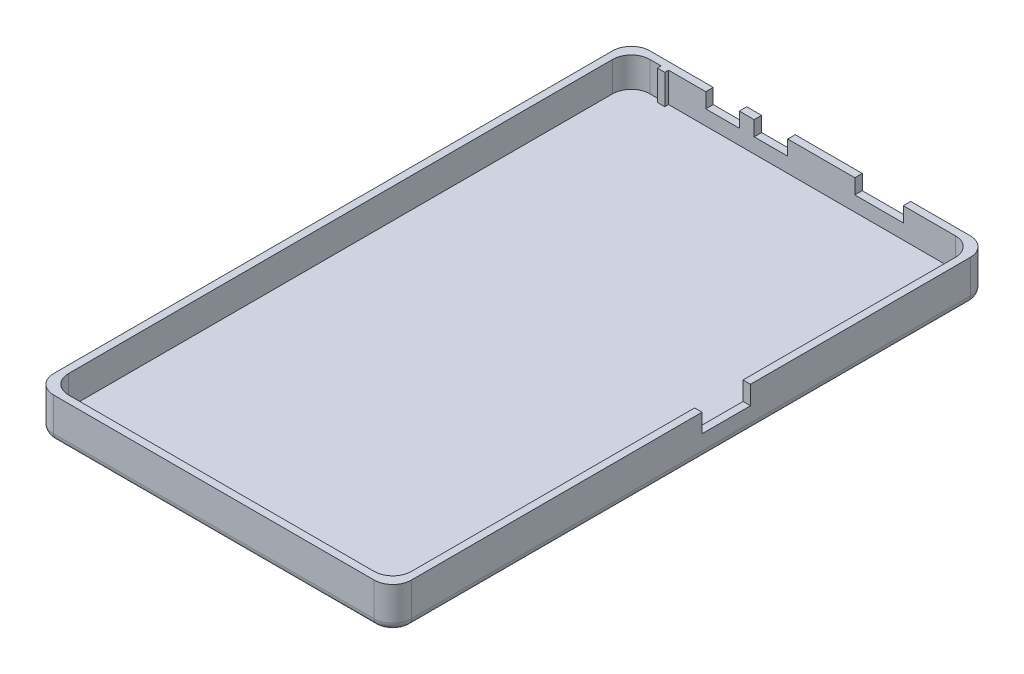
SolidWorks part; units mm, degrees
ref_plane "Front" through (0, 0, 0) normal (0, 0, 1) x (1, 0, 0)
ref_plane "Top" through (0, 0, 0) normal (0, 1, 0) x (1, 0, 0)
ref_plane "Right" through (0, 0, 0) normal (1, 0, 0) x (0, 0, -1)
sketch "草图1" plane through (0, 0, 0) normal (0, 1, 0) x (1, 0, 0)
  line L1 (-48, 80) -> (48, 80)
  line L2 (-48, 80) -> (-48, -80)
  line L3 (-48, -80) -> (48, -80)
  line L4 (48, 80) -> (48, -80)
  line L5 (-48, 80) -> (48, -80) construction
  line L6 (-48, -80) -> (48, 80) construction
  point P0 (0, 0)
  dimension "D1" = 96
  dimension "D2" = 160
extrude "凸台-拉伸1" add sketch "草图1" along normal blind 11
fillet "圆角1" radius 5 1 edges at (-48, 5.5, -80)
fillet "圆角2" radius 5 1 edges at (48, 5.5, -80)
fillet "圆角3" radius 5 1 edges at (48, 5.5, 80)
fillet "圆角4" radius 5 1 edges at (-48, 5.5, 80)
fillet "圆角5" radius 2 8 edges at (-46.5355, 0, 78.5355) (-48, 0, 0) (-46.5355, 0, -78.5355) (0, 0, -80) (46.5355, 0, -78.5355) (48, 0, 0) (46.5355, 0, 78.5355) (0, 0, 80)
sketch "草图2" plane through (0, 11, 0) normal (0, 1, 0) x (1, 0, 0)
  line L0 (-36, 78) -> (41, 78)
  line L1 (-41, 78) -> (-38, 78)
  line L2 (-46, 73) -> (-46, -73)
  line L3 (-41, -78) -> (41, -78)
  line L4 (46, 73) -> (46, -73)
  line L5 (-46, 78) -> (46, -78) construction
  line L6 (-46, -78) -> (46, 78) construction
  line L8 (-38, 78) -> (-38, 77)
  line L9 (-38, 77) -> (-36, 77)
  line L10 (-36, 78) -> (-36, 77)
  arc A0 (-46, 73) -> (-41, 78) centre (-41, 73) cw
  arc A1 (41, 78) -> (46, 73) centre (41, 73) cw
  arc A2 (-41, -78) -> (-46, -73) centre (-41, -73) cw
  arc A3 (41, -78) -> (46, -73) centre (41, -73) ccw
  point P0 (0, 0)
  dimension "D3" = 5
  dimension "D4" = 5
  dimension "D5" = 5
  dimension "D6" = 5
  dimension "D1" = 92
  dimension "D2" = 156
  dimension "D7" = 8
  dimension "D8" = 2
  dimension "D9" = 1
extrude "切除-拉伸1" cut sketch "草图2" against normal blind 8
sketch "草图3" plane through (0, 0, -78) normal (0, 0, 1) x (1, 0, 0)
  line L0 (-36, 3) -> (-36, 11) construction
  line L1 (-26, 11) -> (-17, 11)
  line L2 (-26, 11) -> (-26, 7)
  line L3 (-26, 7) -> (-17, 7)
  line L4 (-17, 11) -> (-17, 7)
  line L6 (-13, 11) -> (-4, 11)
  line L7 (-13, 11) -> (-13, 7)
  line L8 (-13, 7) -> (-4, 7)
  line L9 (-4, 11) -> (-4, 7)
  line L10 (11.7779, 58.6535) -> (20.7779, 58.6535)
  line L11 (11.7779, 58.6535) -> (11.7779, 54.6535)
  line L12 (11.7779, 54.6535) -> (20.7779, 54.6535)
  line L13 (20.7779, 58.6535) -> (20.7779, 54.6535)
  line L14 (14, 11) -> (27, 11)
  line L15 (14, 11) -> (14, 7)
  line L16 (14, 7) -> (27, 7)
  line L17 (27, 11) -> (27, 7)
  line L18 (43, 11) -> (-43, 11) construction
  dimension "D1" = 9
  dimension "D2" = 4
  dimension "D3" = 10
  dimension "D4" = 0
  dimension "D5" = 4
  dimension "D6" = 0
  dimension "D7" = 50
  dimension "D8" = 13
  dimension "D9" = 0
  dimension "D10" = 4
  dimension "D11" = 4
  dimension "D12" = 9
extrude "切除-拉伸2" cut sketch "草图3" against normal blind 4
sketch "草图4" plane through (48, 0, 0) normal (1, 0, 0) x (0, 0, -1)
  line L0 (75, 2) -> (75, 11) construction
  line L1 (3, 11) -> (16, 11)
  line L2 (3, 11) -> (3, 6)
  line L3 (3, 6) -> (16, 6)
  line L4 (16, 11) -> (16, 6)
  line L5 (-75, 11) -> (75, 11) construction
  dimension "D1" = 59
  dimension "D2" = 5
  dimension "D3" = 0
  dimension "D4" = 13
extrude "切除-拉伸3" cut sketch "草图4" against normal blind 5
